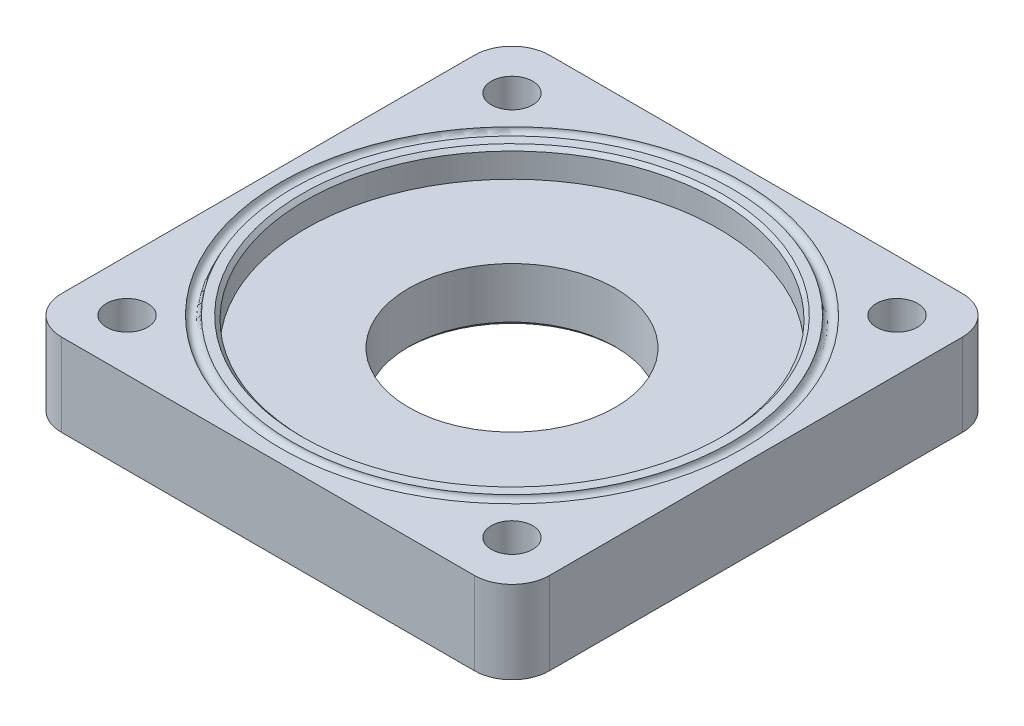
SolidWorks part; units mm, degrees
ref_plane "Front Plane" through (0, 0, 0) normal (0, 0, 1) x (1, 0, 0)
ref_plane "Top Plane" through (0, 0, 0) normal (0, 1, 0) x (1, 0, 0)
ref_plane "Right Plane" through (0, 0, 0) normal (1, 0, 0) x (0, 0, -1)
sketch "Sketch1" plane through (0, 0, 0) normal (0, 1, 0) x (1, 0, 0)
  line L1 (-65, -65) -> (65, -65)
  line L2 (-65, -65) -> (-65, 65)
  line L3 (-65, 65) -> (65, 65)
  line L4 (65, -65) -> (65, 65)
  line L5 (-65, -65) -> (65, 65) construction
  line L6 (-65, 65) -> (65, -65) construction
  circle A0 centre (0, 0) radius 72.5 construction
  circle A1 centre (51.2652, 51.2652) radius 5.5
  circle A2 centre (-51.2652, 51.2652) radius 5.5
  circle A3 centre (51.2652, -51.2652) radius 5.5
  circle A4 centre (-51.2652, -51.2652) radius 5.5
  circle A5 centre (0, 0) radius 27.5
  point P0 (0, 0)
  dimension "D2" = 145
  dimension "D3" = 11
  dimension "D4" = 55
  dimension "D1" = 130
extrude "Boss-Extrude1" add sketch "Sketch1" along normal blind 22
fillet "Fillet1" radius 10 4 edges at (65, 11, -65) (-65, 11, -65) (-65, 11, 65) (65, 11, 65)
sketch "Sketch2" plane through (0, 22, 0) normal (0, 1, 0) x (1, 0, 0)
  circle A0 centre (0, 0) radius 55
  dimension "D1" = 110
extrude "Cut-Extrude1" cut sketch "Sketch2" against normal blind 7.5
sketch "Sketch3" plane through (0, 0, 0) normal (0, -1, 0) x (1, 0, 0)
  circle A0 centre (0, 0) radius 32.5
  dimension "D1" = 65
sketch "Sketch4" plane through (0, 0, 0) normal (0, 0, 1) x (1, 0, 0)
  line L0 (-32.5, 0) -> (32.5, 0) construction
  line L1 (-55, 0) -> (55, 0) construction
  line L2 (0, 0) -> (32.5, 0) construction
  circle A0 centre (32.5, 0) radius 1.5
  dimension "D1" = 3
sweep "Cut-Sweep2" cut profiles "Sketch4" path "Sketch3"
sketch "Sketch6" plane through (0, 0, 0) normal (0, 0, 1) x (1, 0, 0)
  line L0 (-65, 0) -> (-40, 0)
  line L1 (-55, 0) -> (55, 0) construction
  line L2 (-40, 0) -> (-65, 11)
  line L3 (-65, 0) -> (-65, 22) construction
  line L4 (-65, 11) -> (-65, 0)
  dimension "D1" = 25
extrude "Cut-Extrude2" cut sketch "Sketch6" against normal mid plane 45
sketch "Sketch7" plane through (0, 22, 0) normal (0, 1, 0) x (1, 0, 0)
  circle A0 centre (0, 0) radius 60
  dimension "D1" = 120
sketch "Sketch8" plane through (0, 0, 0) normal (0, 0, 1) x (1, 0, 0)
  line L0 (65, 22) -> (55, 22) construction
  circle A0 centre (60, 22) radius 1.5
  dimension "D1" = 3
sweep "Cut-Sweep3" cut profiles "Sketch8" path "Sketch7"
chamfer "Chamfer1" distance 1 angle 45 2 edges at (0, 22, 55) (0, 0, 27.5)
